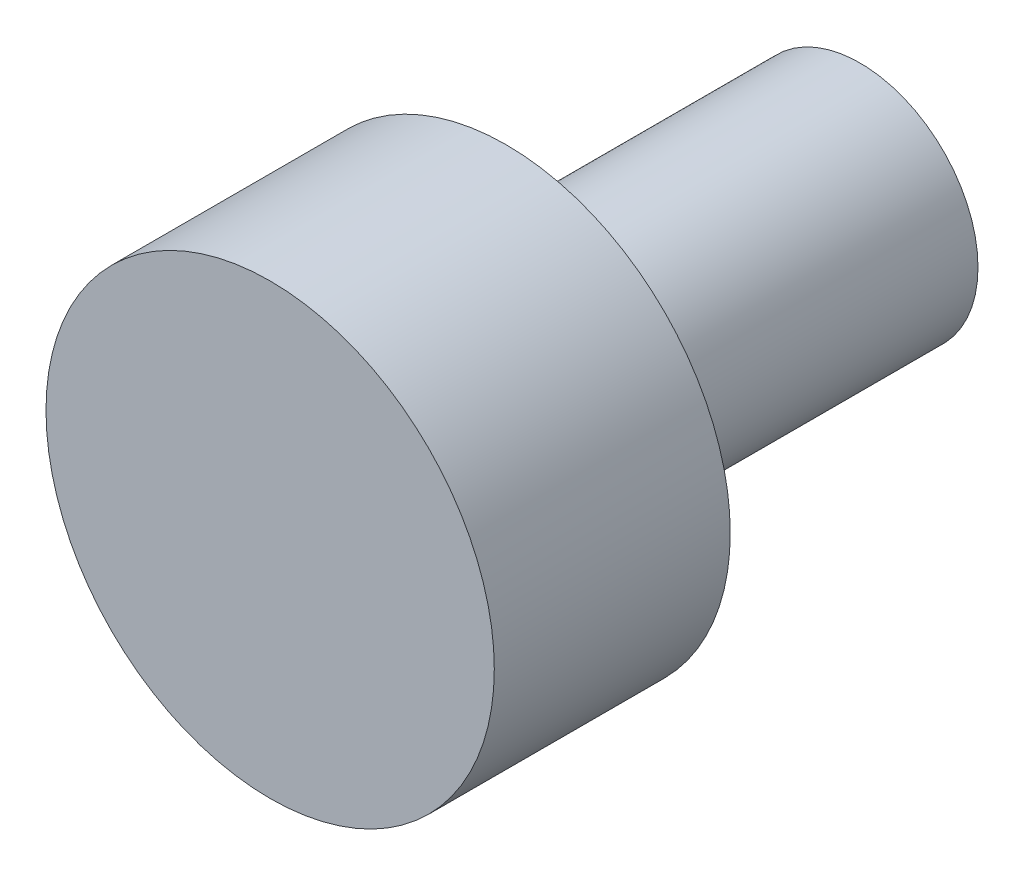
SolidWorks part; units mm, degrees
ref_plane "Front Plane" through (0, 0, 0) normal (0, 0, 1) x (1, 0, 0)
ref_plane "Top Plane" through (0, 0, 0) normal (0, 1, 0) x (1, 0, 0)
ref_plane "Right Plane" through (0, 0, 0) normal (1, 0, 0) x (0, 0, -1)
sketch "Sketch1" plane through (0, 0, 0) normal (0, 0, 1) x (1, 0, 0)
  circle A0 centre (0, 0) radius 1
extrude "Thread_Envelope" add sketch "Sketch1" along normal blind 3 from offset 3
sketch "Sketch2" plane through (0, 0, 0) normal (0, 0, 1) x (1, 0, 0)
  circle A0 centre (0, 0) radius 1.9
extrude "Head_Envelope" add sketch "Sketch2" along normal blind 2
